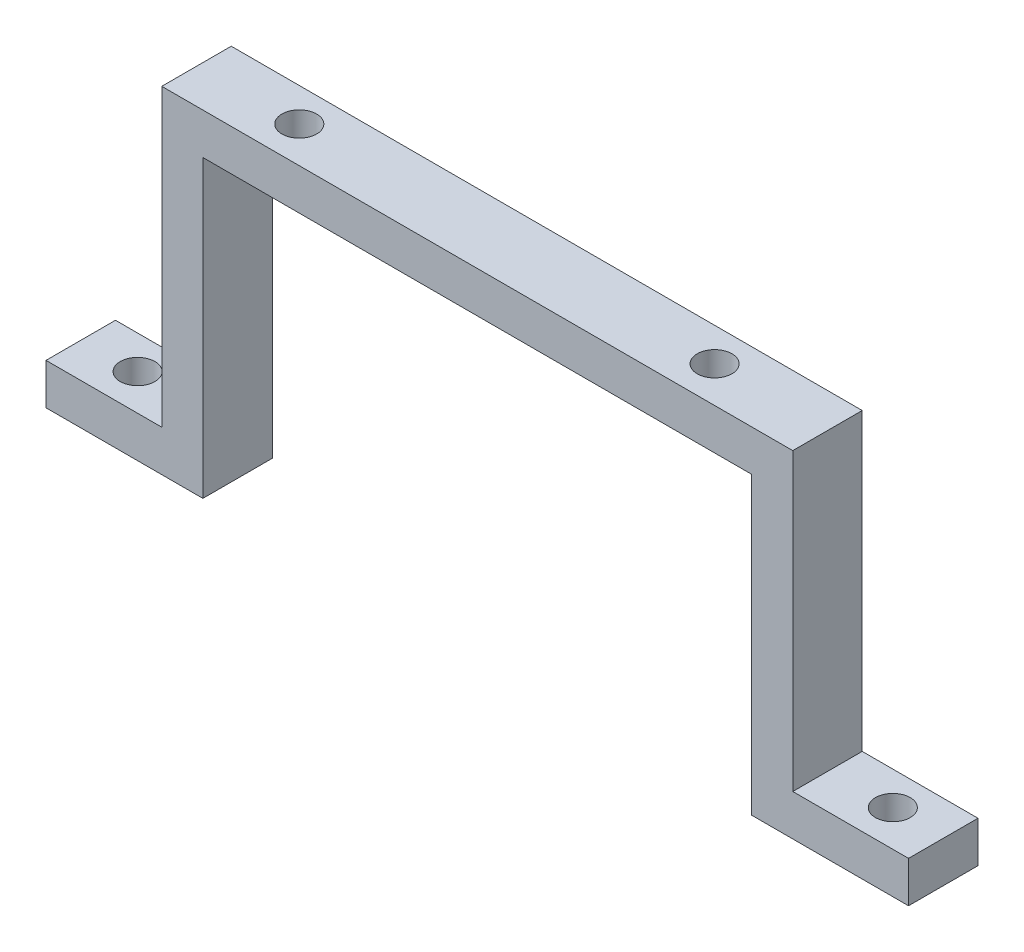
SolidWorks part; units mm, degrees
ref_plane "Front Plane" through (0, 0, 0) normal (0, 0, 1) x (1, 0, 0)
ref_plane "Top Plane" through (0, 0, 0) normal (0, 1, 0) x (1, 0, 0)
ref_plane "Right Plane" through (0, 0, 0) normal (1, 0, 0) x (0, 0, -1)
sketch "Sketch1" plane through (0, 0, 0) normal (0, 0, 1) x (1, 0, 0)
  line L0 (-12.4327, 0) -> (-2.4327, 0)
  line L1 (-2.4327, 0) -> (-2.4327, 25.5)
  line L2 (-2.4327, 25.5) -> (52.0673, 25.5)
  line L3 (52.0673, 25.5) -> (52.0673, 0)
  line L4 (52.0673, 0) -> (62.0673, 0)
  dimension "D1" = 10
  dimension "D2" = 10
  dimension "D3" = 25.5
  dimension "D4" = 54.5
extrude "Extrude-Thin4" add sketch "Sketch1" along normal blind 6 thin
sketch "Sketch3" plane through (0, 0, 0) normal (0, 1, 0) x (1, 0, 0)
  circle A0 centre (-7.6396, -2.881) radius 1.5
  circle A1 centre (6.3272, -2.881) radius 1.5
  circle A2 centre (42.1964, -2.881) radius 1.5
  circle A3 centre (57.5916, -2.881) radius 1.5
  dimension "D1" = 3
  dimension "D2" = 3
  dimension "D3" = 3
  dimension "D4" = 3
extrude "Cut-Extrude1" cut sketch "Sketch3" against normal blind 28 and the other way blind 41
